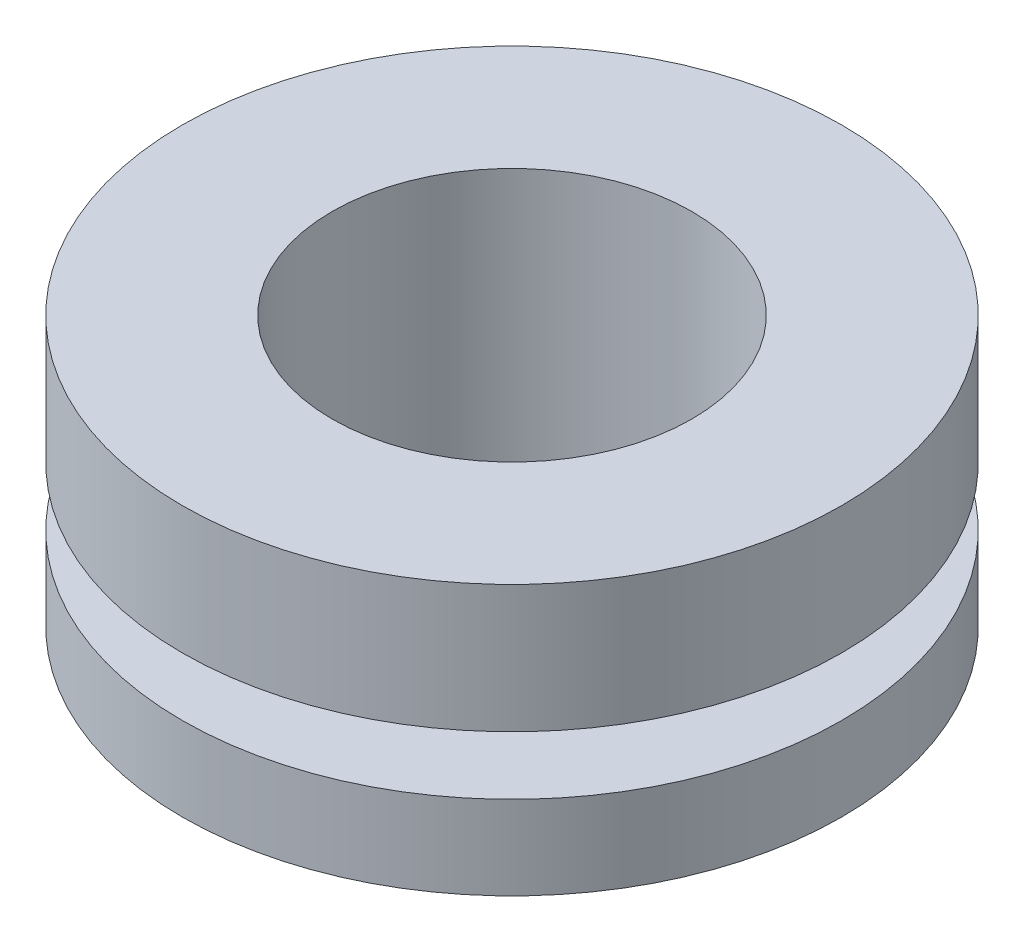
SolidWorks part; units mm, degrees
ref_plane "前视基准面" through (0, 0, 0) normal (0, 0, 1) x (1, 0, 0)
ref_plane "上视基准面" through (0, 0, 0) normal (0, 1, 0) x (1, 0, 0)
ref_plane "右视基准面" through (0, 0, 0) normal (1, 0, 0) x (0, 0, -1)
sketch "草图1" plane through (0, 0, 0) normal (0, 1, 0) x (1, 0, 0)
  circle A0 centre (0, 0) radius 3
  circle A1 centre (0, 0) radius 5.5
  dimension "D1" = 6
  dimension "D2" = 11
extrude "凸台-拉伸1" add sketch "草图1" along normal blind 4.5
sketch "草图2" plane through (0, 0, 0) normal (0, 0, 1) x (1, 0, 0)
  line L0 (-5.5, 2.3713) -> (-3.8068, 2.3713)
  line L1 (-5.5, 4.5) -> (-5.5, 0) construction
  line L2 (-3.8068, 2.3713) -> (-3.8068, 1.3954)
  line L3 (-3.8068, 1.3954) -> (-5.5, 1.3954)
  line L4 (-5.5, 1.3954) -> (-5.5, 2.3713)
ref_axis "基准轴1" through (0, 4.5, 0) along (0, -1, 0)
revolve "切除-旋转1" cut sketch "草图2" angle 360 about axis through (0, 4.5, 0) along (0, -1, 0)
